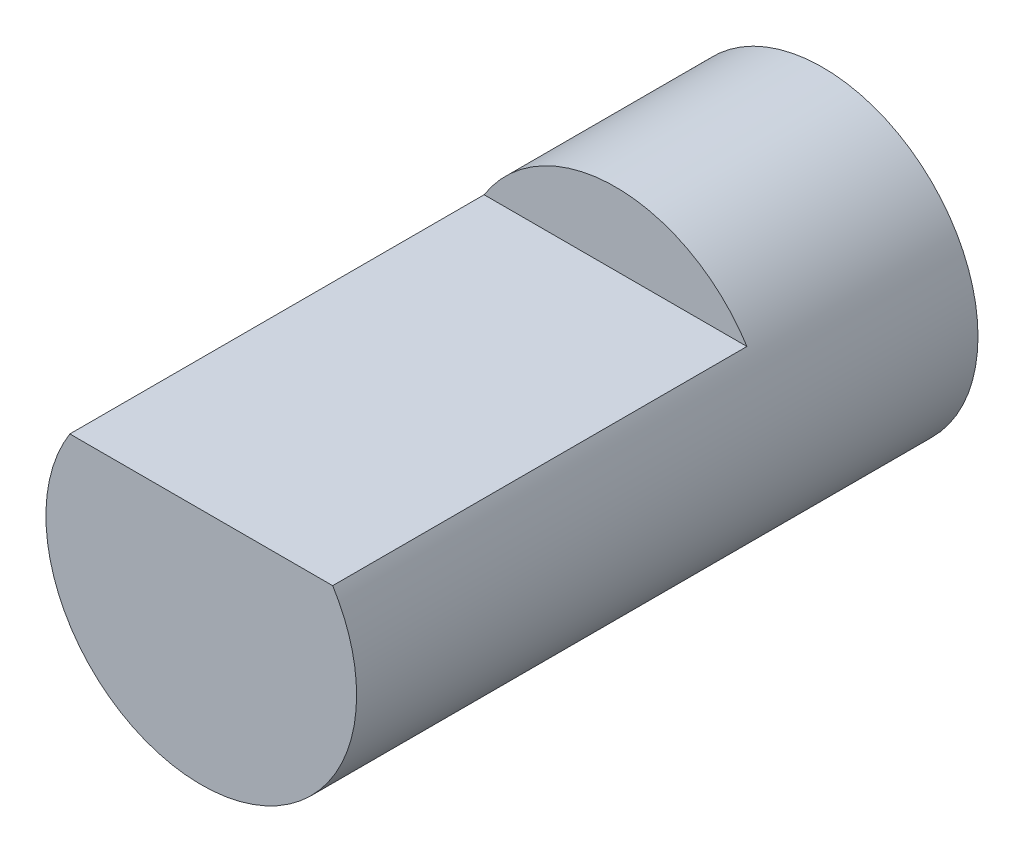
SolidWorks part; units mm, degrees
ref_plane "Frontal Plane" through (0, 0, 0) normal (0, 0, 1) x (1, 0, 0)
ref_plane "Horizontal Plane" through (0, 0, 0) normal (0, 1, 0) x (1, 0, 0)
ref_plane "Profile Plane" through (0, 0, 0) normal (1, 0, 0) x (0, 0, -1)
sketch "Sketch1" plane through (0, 0, 0) normal (0, 0, 1) x (1, 0, 0)
  circle A0 centre (0, 0) radius 7.5
  dimension "D1" = 15
extrude "Boss-Extrude1" add sketch "Sketch1" against normal blind 30
sketch "Sketch2" plane through (0, 0, 0) normal (0, 0, 1) x (1, 0, 0)
  line L0 (-6.3443, 4) -> (6.3443, 4)
  circle A0 centre (0, 0) radius 7.5 construction
  arc A1 (-6.3443, 4) -> (6.3443, 4) centre (0, 0) cw
  dimension "D1" = 4
extrude "Cut-Extrude1" cut sketch "Sketch2" against normal blind 20
equation "\"PinDiameter\"= 0"
equation "\"WallThickness\"= 0.5cm"
equation "\"ActuatorL\"= 35cm"
equation "\"Box-X\"= 40cm"
equation "\"Box-Z\"= 20cm"
equation "\"Box-Y\"= 30cm"
equation "\"BottomPlateX\"= 100cm"
equation "\"ArmPlateThickness\"= 1cm"
equation "\"ArmPlateX\"= 50cm"
equation "\"Arm1X\"= 5cm"
equation "\"Arm1L\"= 60cm"
equation "\"Arm2GAP\"= 5cm"
equation "\"Arm2L\"= 60cm"
equation "\"Arm2H\"= 5cm"
equation "\"Arm2Extension\"= 5cm"
equation "\"Arm3GAP\"= 5cm"
equation "\"Arm3L\"= 60cm"
equation "\"Arm3H\"= 5cm"
equation "\"Pin1-2L\"= \"Arm2GAP\" + (2 * \"WallThickness\")"
equation "\"Pin2-3L\"= \"Arm3GAP\" + (4 * \"WallThickness\")"
equation "\"DCMotor2X\"= 68mm"
equation "\"DCMotor2D\"= 65mm"
equation "\"DCMotor2L\"= 208mm"
equation "\"DCMotor2ShaftL\"= 30mm"
equation "\"D1@Boss-Extrude1\"=\"DCMotor1ShaftL\""
equation "\"RotaryUnionThickness\"= 1cm"
equation "\"D1@Cut-Extrude1\"=\"ArmPlateThickness\"+\"RotaryUnionThickness\""
equation "\"DCMotor1D\"= 65mm"
equation "\"BenchDepth\"= 5cm"
equation "\"BenchH\"= 10cm"
equation "\"BenchL\"= 15cm"
equation "\"DCMotor1ShaftL\"= 30mm"
equation "\"DCMotor1L\"= 215mm"
